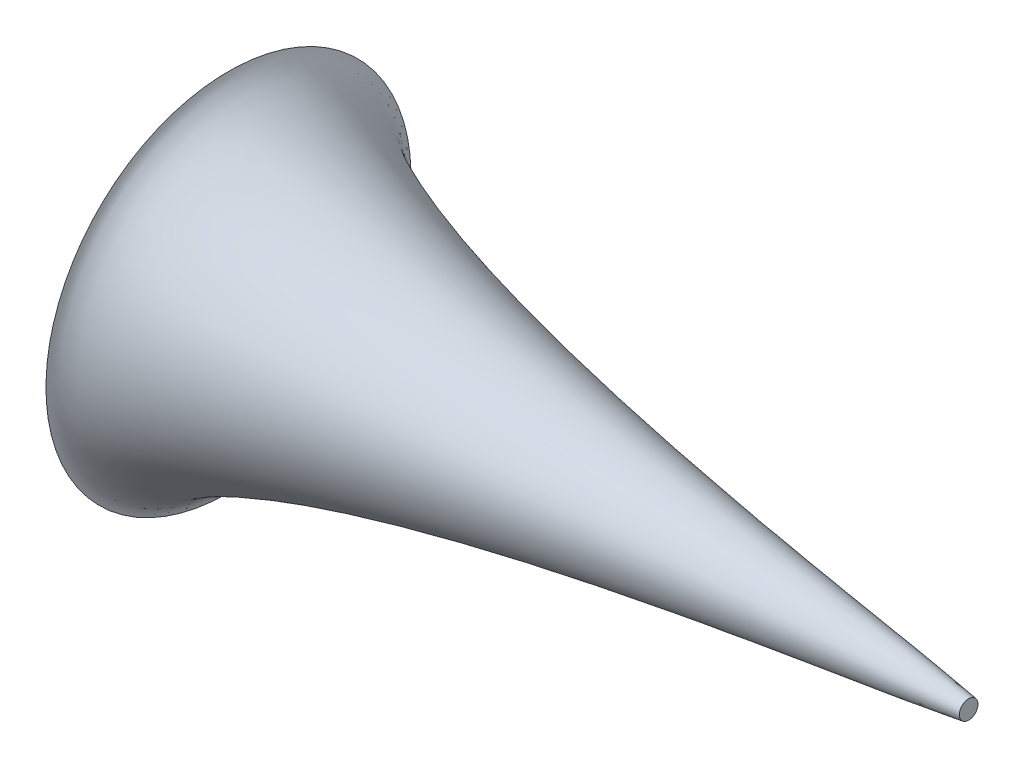
SolidWorks part; units mm, degrees
ref_plane "Front Plane" through (0, 0, 0) normal (0, 0, 1) x (1, 0, 0)
ref_plane "Top Plane" through (0, 0, 0) normal (0, 1, 0) x (1, 0, 0)
ref_plane "Right Plane" through (0, 0, 0) normal (1, 0, 0) x (0, 0, -1)
curve "Curve1"
  spline degree 3 poles (102.6028, 1.2964, 0) (101.3078, 1.486, 0) (99.0891, 1.8109, 0) (95.9828, 2.2484, 0) (93.2934, 2.6069, 0) (90.661, 2.9465, 0) (88.0029, 3.2776, 0) (85.3354, 3.6191, 0) (82.6979, 3.9643, 0) (80.1628, 4.2975, 0) (77.7185, 4.6202, 0) (75.2874, 4.9418, 0) (72.8844, 5.2716, 0) (70.5262, 5.5997, 0) (68.2557, 5.9202, 0) (66.0138, 6.24, 0) (63.8059, 6.5651, 0) (61.6414, 6.8898, 0) (59.5399, 7.21, 0) (57.4742, 7.5317, 0) (55.4457, 7.8558, 0) (53.4725, 8.1776, 0) (51.5379, 8.4981, 0) (49.6422, 8.8217, 0) (47.7856, 9.1457, 0) (45.9767, 9.4673, 0) (44.2081, 9.7903, 0) (42.479, 10.1138, 0) (40.7925, 10.4358, 0) (39.147, 10.7584, 0) (37.5417, 11.0809, 0) (35.9754, 11.4024, 0) (34.4505, 11.724, 0) (32.9642, 12.0453, 0) (31.5164, 12.3653, 0) (30.1102, 12.6851, 0) (28.7374, 13.0047, 0) (27.4068, 13.3225, 0) (26.1173, 13.6389, 0) (24.8603, 13.9546, 0) (23.645, 14.2688, 0) (22.4615, 14.5824, 0) (21.3186, 14.8935, 0) (20.2138, 15.2026, 0) (19.1419, 15.5103, 0) (18.1113, 15.8148, 0) (17.109, 16.1186, 0) (16.1481, 16.4186, 0) (15.2153, 16.7177, 0) (14.3225, 17.0126, 0) (13.4596, 17.3055, 0) (12.6337, 17.5944, 0) (11.838, 17.8807, 0) (11.0774, 18.1628, 0) (10.3465, 18.442, 0) (9.6498, 18.7164, 0) (8.9811, 18.9878, 0) (8.3469, 19.2536, 0) (7.738, 19.5166, 0) (7.1633, 19.7732, 0) (6.6118, 20.0274, 0) (6.0925, 20.2748, 0) (5.5974, 20.5186, 0) (5.1311, 20.7562, 0) (4.6925, 20.9876, 0) (4.2768, 21.2147, 0) (3.8878, 21.4351, 0) (3.5202, 21.651, 0) (3.1775, 21.86, 0) (2.858, 22.0624, 0) (2.5591, 22.2592, 0) (2.2817, 22.4494, 0) (2.0244, 22.6332, 0) (1.7866, 22.8103, 0) (1.5672, 22.981, 0) (1.3649, 23.1454, 0) (1.1811, 23.302, 0) (1.0126, 23.4525, 0) (0.8585, 23.597, 0) (0.7194, 23.7342, 0) (0.5951, 23.8636, 0) (0.4824, 23.9877, 0) (0.3805, 24.1064, 0) (0.2909, 24.2174, 0) (0.2133, 24.3199, 0) (0.1441, 24.4179, 0) (0.0821, 24.512, 0) (0.028, 24.6006, 0) (-0.0172, 24.6809, 0) (-0.0545, 24.7534, 0) (-0.0865, 24.8221, 0) (-0.1695, 25.0194, 0) (-0.2117, 25.2049, 0) (-0.2484, 25.3665, 0) knots 0 0 0 0 0.036699 0.062878 0.087959 0.112775 0.137302 0.163069 0.188182 0.211888 0.234764 0.257314 0.280651 0.302776 0.324077 0.344946 0.366274 0.386655 0.406315 0.425881 0.445276 0.463916 0.481939 0.500263 0.51784 0.534785 0.551778 0.568253 0.58411 0.599921 0.61527 0.630023 0.644756 0.658968 0.672663 0.68633 0.699406 0.712185 0.724691 0.736634 0.748527 0.759886 0.770965 0.781738 0.792055 0.802236 0.811869 0.821422 0.830463 0.839337 0.847784 0.856016 0.863871 0.871495 0.878761 0.885811 0.892489 0.898997 0.905091 0.911088 0.916646 0.922118 0.927218 0.932119 0.936792 0.941123 0.945401 0.949329 0.953075 0.956656 0.959933 0.96311 0.966087 0.968798 0.971423 0.973881 0.976107 0.978194 0.980214 0.982032 0.983669 0.985246 0.98673 0.988056 0.989244 0.990334 0.991421 0.992402 0.993245 0.994004 0.994687 0.995372 1 1 1 1
sketch "Sketch1" plane through (0, 0, 0) normal (0, 0, 1) x (1, 0, 0)
  line L0 (-0.2484, 25.3665) -> (-0.2484, 0)
  line L1 (-0.2484, 0) -> (102.6028, 0)
  line L2 (102.6028, 0) -> (102.6028, 1.2964)
  spline S0 degree 3 poles (480.2553, 927.2406) (257.9932, -37.4468) (178.6293, -9.3903) (95.9828, 2.2484) (93.2934, 2.6069) (90.661, 2.9465) (88.0029, 3.2776) (85.3354, 3.6191) (82.6979, 3.9643) (80.1628, 4.2975) (77.7185, 4.6202) (75.2874, 4.9418) (72.8844, 5.2716) (70.5262, 5.5997) (68.2557, 5.9202) (66.0138, 6.24) (63.8059, 6.5651) (61.6414, 6.8898) (59.5399, 7.21) (57.4742, 7.5317) (55.4457, 7.8558) (53.4725, 8.1776) (51.5379, 8.4981) (49.6422, 8.8217) (47.7856, 9.1457) (45.9767, 9.4673) (44.2081, 9.7903) (42.479, 10.1138) (40.7925, 10.4358) (39.147, 10.7584) (37.5417, 11.0809) (35.9754, 11.4024) (34.4505, 11.724) (32.9642, 12.0453) (31.5164, 12.3653) (30.1102, 12.6851) (28.7374, 13.0047) (27.4068, 13.3225) (26.1173, 13.6389) (24.8603, 13.9546) (23.645, 14.2688) (22.4615, 14.5824) (21.3186, 14.8935) (20.2138, 15.2026) (19.1419, 15.5103) (18.1113, 15.8148) (17.109, 16.1186) (16.1481, 16.4186) (15.2153, 16.7177) (14.3225, 17.0126) (13.4596, 17.3055) (12.6337, 17.5944) (11.838, 17.8807) (11.0774, 18.1628) (10.3465, 18.442) (9.6498, 18.7164) (8.9811, 18.9878) (8.3469, 19.2536) (7.738, 19.5166) (7.1633, 19.7732) (6.6118, 20.0274) (6.0925, 20.2748) (5.5974, 20.5186) (5.1311, 20.7562) (4.6925, 20.9876) (4.2768, 21.2147) (3.8878, 21.4351) (3.5202, 21.651) (3.1775, 21.86) (2.858, 22.0624) (2.5591, 22.2592) (2.2817, 22.4494) (2.0244, 22.6332) (1.7866, 22.8103) (1.5672, 22.981) (1.3649, 23.1454) (1.1811, 23.302) (1.0126, 23.4525) (0.8585, 23.597) (0.7194, 23.7342) (0.5951, 23.8636) (0.4824, 23.9877) (0.3805, 24.1064) (0.2909, 24.2174) (0.2133, 24.3199) (0.1441, 24.4179) (0.0821, 24.512) (0.028, 24.6006) (-0.0172, 24.6809) (-0.0545, 24.7534) (-0.0865, 24.8221) (-2.357, 30.2163) (25.0307, 45.7557) (-951.4398, -282.9908) knots -2.252299 -2.252299 -2.252299 -2.252299 0.036699 0.062878 0.087959 0.112775 0.137302 0.163069 0.188182 0.211888 0.234764 0.257314 0.280651 0.302776 0.324077 0.344946 0.366274 0.386655 0.406315 0.425881 0.445276 0.463916 0.481939 0.500263 0.51784 0.534785 0.551778 0.568253 0.58411 0.599921 0.61527 0.630023 0.644756 0.658968 0.672663 0.68633 0.699406 0.712185 0.724691 0.736634 0.748527 0.759886 0.770965 0.781738 0.792055 0.802236 0.811869 0.821422 0.830463 0.839337 0.847784 0.856016 0.863871 0.871495 0.878761 0.885811 0.892489 0.898997 0.905091 0.911088 0.916646 0.922118 0.927218 0.932119 0.936792 0.941123 0.945401 0.949329 0.953075 0.956656 0.959933 0.96311 0.966087 0.968798 0.971423 0.973881 0.976107 0.978194 0.980214 0.982032 0.983669 0.985246 0.98673 0.988056 0.989244 0.990334 0.991421 0.992402 0.993245 0.994004 0.994687 0.995372 1.15799 1.15799 1.15799 1.15799 only from (102.6028, 1.2964) to (-0.2484, 25.3665) construction
  spline S1 degree 3 poles (102.6028, 1.2964) (101.3078, 1.486) (99.0891, 1.8109) (95.9828, 2.2484) (93.2934, 2.6069) (90.661, 2.9465) (88.0029, 3.2776) (85.3354, 3.6191) (82.6979, 3.9643) (80.1628, 4.2975) (77.7185, 4.6202) (75.2874, 4.9418) (72.8844, 5.2716) (70.5262, 5.5997) (68.2557, 5.9202) (66.0138, 6.24) (63.8059, 6.5651) (61.6414, 6.8898) (59.5399, 7.21) (57.4742, 7.5317) (55.4457, 7.8558) (53.4725, 8.1776) (51.5379, 8.4981) (49.6422, 8.8217) (47.7856, 9.1457) (45.9767, 9.4673) (44.2081, 9.7903) (42.479, 10.1138) (40.7925, 10.4358) (39.147, 10.7584) (37.5417, 11.0809) (35.9754, 11.4024) (34.4505, 11.724) (32.9642, 12.0453) (31.5164, 12.3653) (30.1102, 12.6851) (28.7374, 13.0047) (27.4068, 13.3225) (26.1173, 13.6389) (24.8603, 13.9546) (23.645, 14.2688) (22.4615, 14.5824) (21.3186, 14.8935) (20.2138, 15.2026) (19.1419, 15.5103) (18.1113, 15.8148) (17.109, 16.1186) (16.1481, 16.4186) (15.2153, 16.7177) (14.3225, 17.0126) (13.4596, 17.3055) (12.6337, 17.5944) (11.838, 17.8807) (11.0774, 18.1628) (10.3465, 18.442) (9.6498, 18.7164) (8.9811, 18.9878) (8.3469, 19.2536) (7.738, 19.5166) (7.1633, 19.7732) (6.6118, 20.0274) (6.0925, 20.2748) (5.5974, 20.5186) (5.1311, 20.7562) (4.6925, 20.9876) (4.2768, 21.2147) (3.8878, 21.4351) (3.5202, 21.651) (3.1775, 21.86) (2.858, 22.0624) (2.5591, 22.2592) (2.2817, 22.4494) (2.0244, 22.6332) (1.7866, 22.8103) (1.5672, 22.981) (1.3649, 23.1454) (1.1811, 23.302) (1.0126, 23.4525) (0.8585, 23.597) (0.7194, 23.7342) (0.5951, 23.8636) (0.4824, 23.9877) (0.3805, 24.1064) (0.2909, 24.2174) (0.2133, 24.3199) (0.1441, 24.4179) (0.0821, 24.512) (0.028, 24.6006) (-0.0172, 24.6809) (-0.0545, 24.7534) (-0.0865, 24.8221) (-0.1695, 25.0194) (-0.2117, 25.2049) (-0.2484, 25.3665) knots 0 0 0 0 0.036699 0.062878 0.087959 0.112775 0.137302 0.163069 0.188182 0.211888 0.234764 0.257314 0.280651 0.302776 0.324077 0.344946 0.366274 0.386655 0.406315 0.425881 0.445276 0.463916 0.481939 0.500263 0.51784 0.534785 0.551778 0.568253 0.58411 0.599921 0.61527 0.630023 0.644756 0.658968 0.672663 0.68633 0.699406 0.712185 0.724691 0.736634 0.748527 0.759886 0.770965 0.781738 0.792055 0.802236 0.811869 0.821422 0.830463 0.839337 0.847784 0.856016 0.863871 0.871495 0.878761 0.885811 0.892489 0.898997 0.905091 0.911088 0.916646 0.922118 0.927218 0.932119 0.936792 0.941123 0.945401 0.949329 0.953075 0.956656 0.959933 0.96311 0.966087 0.968798 0.971423 0.973881 0.976107 0.978194 0.980214 0.982032 0.983669 0.985246 0.98673 0.988056 0.989244 0.990334 0.991421 0.992402 0.993245 0.994004 0.994687 0.995372 1 1 1 1
revolve "Revolve1" add sketch "Sketch1" angle 360 about L1
